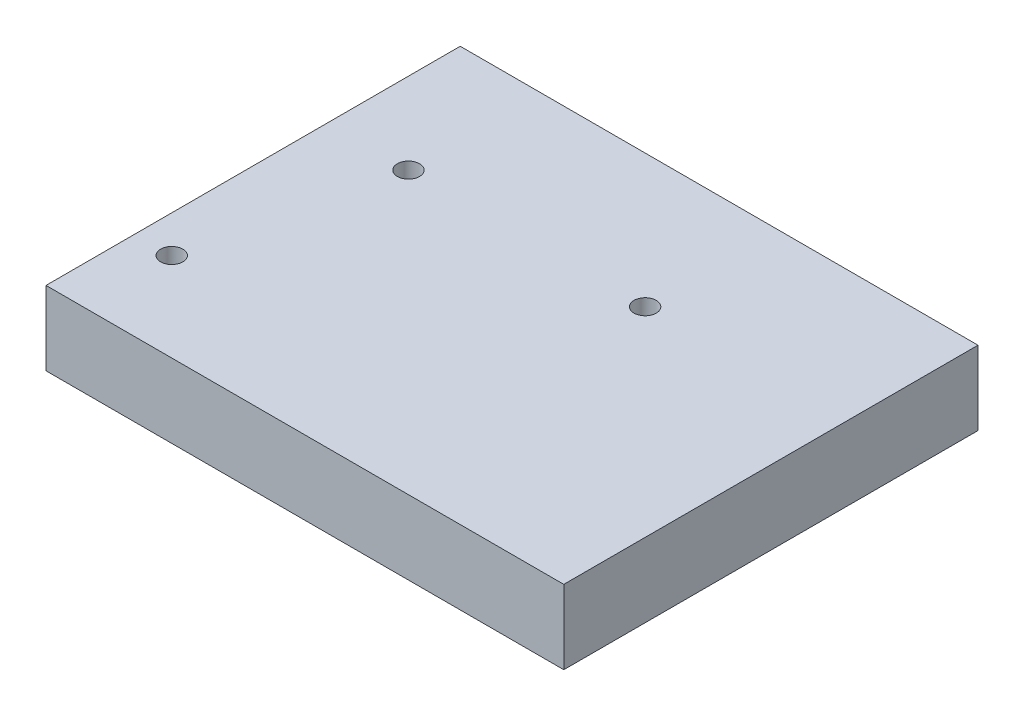
SolidWorks part; units mm, degrees
ref_plane "Front Plane" through (0, 0, 0) normal (0, 0, 1) x (1, 0, 0)
ref_plane "Top Plane" through (0, 0, 0) normal (0, 1, 0) x (1, 0, 0)
ref_plane "Right Plane" through (0, 0, 0) normal (1, 0, 0) x (0, 0, -1)
sketch "Sketch1" plane through (0, 0, 0) normal (0, 1, 0) x (1, 0, 0)
  line L1 (-35, 28) -> (35, 28)
  line L2 (-35, 28) -> (-35, -28)
  line L3 (-35, -28) -> (35, -28)
  line L4 (35, 28) -> (35, -28)
  line L5 (-35, 28) -> (35, -28) construction
  line L6 (-35, -28) -> (35, 28) construction
  point P0 (0, 0)
  dimension "D1" = 70
  dimension "D2" = 56
extrude "Boss-Extrude1" add sketch "Sketch1" along normal blind 10
sketch "Sketch2" plane through (0, 10, 0) normal (0, 1, 0) x (1, 0, 0)
  line L0 (-35, 28) -> (-35, -28) construction
  line L1 (-35, -28) -> (35, -28) construction
  circle A0 centre (-30, -16) radius 1.5
  circle A1 centre (-24, 10) radius 1.5
  circle A2 centre (8, 10) radius 1.5
  dimension "D1" = 3
  dimension "D2" = 5
  dimension "D3" = 12
  dimension "D4" = 26
  dimension "D5" = 6
  dimension "D6" = 32
extrude "Cut-Extrude1" cut sketch "Sketch2" against normal blind 10
